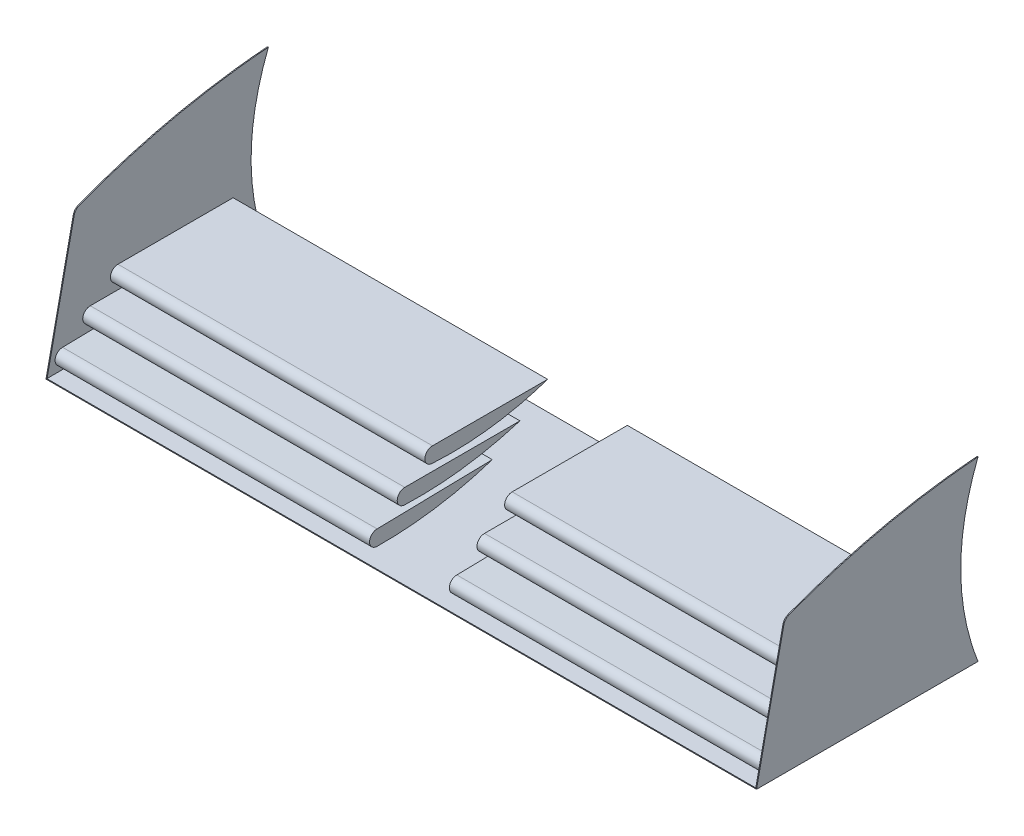
SolidWorks part; units mm, degrees
ref_plane "Front Plane" through (0, 0, 0) normal (0, 0, 1) x (1, 0, 0)
ref_plane "Top Plane" through (0, 0, 0) normal (0, 1, 0) x (1, 0, 0)
ref_plane "Right Plane" through (0, 0, 0) normal (1, 0, 0) x (0, 0, -1)
sketch "Sketch1" plane through (0, 0, 0) normal (1, 0, 0) x (0, 0, -1)
  line L1 (0, 0) -> (635, 0)
  line L2 (0, 0) -> (0, 508)
  line L3 (0, 508) -> (635, 508)
  line L4 (635, 0) -> (635, 508)
  dimension "D1" = 508
  dimension "D2" = 635
extrude "Boss-Extrude1" add sketch "Sketch1" along normal blind 2.54 from offset 1016
mirror "Mirror2" about plane through (0, 0, 0) normal (1, 0, 0) of bodies 101
sketch "Sketch2" plane through (0, 0, 0) normal (1, 0, 0) x (0, 0, -1)
  line L0 (635, 508) -> (635, 0)
  spline S0 degree 2 poles (635, 508) (535.9785, 253.9497) (635, 0) knots 0 0 0 1 1 1
extrude "Cut-Extrude1" cut sketch "Sketch2" against normal through all both and the other way through all
sketch "Sketch3" plane through (0, 0, 0) normal (1, 0, 0) x (0, 0, -1)
  line L0 (0, 0) -> (78.1261, 368.5424)
  line L2 (0, 0) -> (0, 508)
  line L3 (0, 508) -> (635, 508)
  arc A0 (93.9896, 387.033) -> (78.1261, 368.5424) centre (102.9739, 363.275) ccw
  spline S0 degree 3 poles (635, 508) (448.7015, 493.2828) (268.258, 452.9341) (93.9896, 387.033) knots 0 0 0 0 0.975723 0.975723 0.975723 0.975723
  dimension "D1" = 25.4
extrude "Cut-Extrude2" cut sketch "Sketch3" against normal through all both and the other way through all
sketch "Sketch4" plane through (0, 0, 0) normal (1, 0, 0) x (0, 0, -1)
  line L0 (0, 0) -> (635, 508) construction
  line L1 (45.0812, 57.7248) -> (375.2812, 64.5745)
  line L2 (124.4174, 121.1938) -> (454.6174, 121.1938)
  line L3 (203.7537, 184.6629) -> (533.9537, 184.6629)
  arc A0 (45.0812, 57.7248) -> (45.0812, 14.405) centre (45.0812, 36.0649) ccw
  arc A1 (124.4174, 121.1938) -> (124.4174, 77.8741) centre (124.4174, 99.5339) ccw
  arc A2 (203.7537, 184.6629) -> (203.7537, 141.3431) centre (203.7537, 163.003) ccw
  spline S0 degree 2 poles (375.2812, 64.5745) (213.9845, 12.3103) (45.0812, 14.405) knots 0 0 0 1 1 1
  spline S1 degree 2 poles (454.6174, 121.1938) (292.9345, 71.3161) (124.4174, 77.8741) knots 0 0 0 1 1 1
  spline S2 degree 2 poles (203.7537, 141.3431) (373.0548, 130.6686) (533.9537, 184.6629) knots 0 0 0 1 1 1
  point P18 (368.8537, 184.6629)
  dimension "D1" = 38.1
  dimension "D2" = 38.1
  dimension "D3" = 330.2
  dimension "D4" = 38.1
  dimension "D5" = 330.2
  dimension "D6" = 330.2
  dimension "D7" = 101.6
  dimension "D8" = 101.6
extrude "Boss-Extrude2" add sketch "Sketch4" along normal up to body (1016 mm away) and the other way up to body (1018.54 mm away) separate body
sketch "Sketch6" plane through (0, 0, 0) normal (0, 1, 0) x (1, 0, 0)
  line L1 (-1018.54, 0) -> (1018.54, 0)
  line L2 (-1018.54, 0) -> (-1018.54, 635)
  line L3 (-1018.54, 635) -> (1018.54, 635)
  line L4 (1018.54, 0) -> (1018.54, 635)
extrude "Boss-Extrude3" add sketch "Sketch6" along normal blind 2.54 separate body
sketch "Sketch7" plane through (0, 184.6629, 0) normal (0, 1, 0) x (1, 0, 0)
  line L0 (-114.3, 635) -> (-114.3, 0)
  line L1 (1018.54, 635) -> (-1018.54, 635) construction
  line L2 (-1018.54, 0) -> (1018.54, 0) construction
  line L3 (114.3, 635) -> (114.3, 0)
  line L4 (0, 0) -> (0, 635) construction
  line L5 (-114.3, 635) -> (114.3, 635)
  line L6 (-114.3, 0) -> (114.3, 0)
  dimension "D3" = 114.3
  dimension "D4" = 114.3
extrude "Cut-Extrude3" cut sketch "Sketch7" against normal up to surface (182.1229 mm away) up to face at (0, 2.54, -317.351)
scale "Scale1" scale about centroid uniform scaling yes scale factor 0.15
